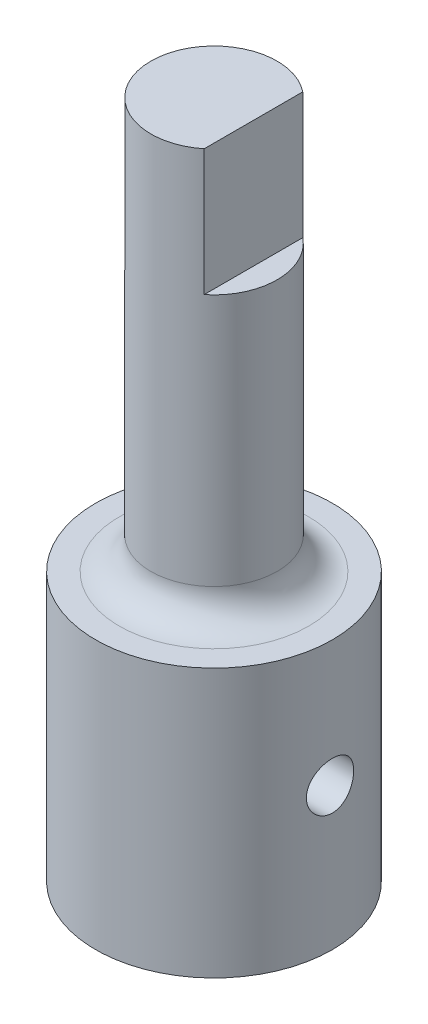
SolidWorks part; units mm, degrees
ref_plane "Plan de face" through (0, 0, 0) normal (0, 0, 1) x (1, 0, 0)
ref_plane "Plan de dessus" through (0, 0, 0) normal (0, 1, 0) x (1, 0, 0)
ref_plane "Plan de droite" through (0, 0, 0) normal (1, 0, 0) x (0, 0, -1)
sketch "Esquisse1" plane through (0, 0, 0) normal (0, 0, 1) x (1, 0, 0)
  line L0 (0, 0) -> (4, 0)
  line L1 (4, 0) -> (4, -26)
  line L2 (4, -26) -> (7.5, -26)
  line L3 (7.5, -26) -> (7.5, -43)
  line L4 (7.5, -43) -> (3, -43)
  line L5 (3, -43) -> (3, -29)
  line L6 (3, -29) -> (0, -26)
  line L7 (0, -26) -> (0, 0)
  line L8 (0, -26) -> (0, -43) construction
  dimension "D1" = 45
  dimension "D2" = 8
  dimension "D3" = 6
  dimension "D4" = 14
  dimension "D5" = 3
  dimension "D6" = 26
  dimension "D7" = 15
  dimension "D8" = 4.5
  dimension "D9" = 43
revolve "Révolution1" add sketch "Esquisse1" angle 360 about L8
fillet "Congé1" radius 2 1 edges at (-4, -26, 0)
sketch "Esquisse2" plane through (0, 0, 0) normal (0, 1, 0) x (1, 0, 0)
  line L1 (2.5, 3.1225) -> (4, 3.1225)
  line L2 (2.5, 3.1225) -> (2.5, -3.1225)
  line L3 (2.5, -3.1225) -> (4, -3.1225)
  line L4 (4, 3.1225) -> (4, -3.1225)
  circle A0 centre (0, 0) radius 4 construction
  dimension "D1" = 2.5
extrude "Enlèv. mat.-Extru.1" cut sketch "Esquisse2" against normal blind 8
sketch "Esquisse3" plane through (0, 0, 0) normal (1, 0, 0) x (0, 0, -1)
  line L0 (-7.5, -43) -> (7.5, -43) construction
  circle A0 centre (0, -34) radius 1.5
  dimension "D1" = 9
  dimension "D2" = 3
extrude "Enlèv. mat.-Extru.2" cut sketch "Esquisse3" along normal through all
